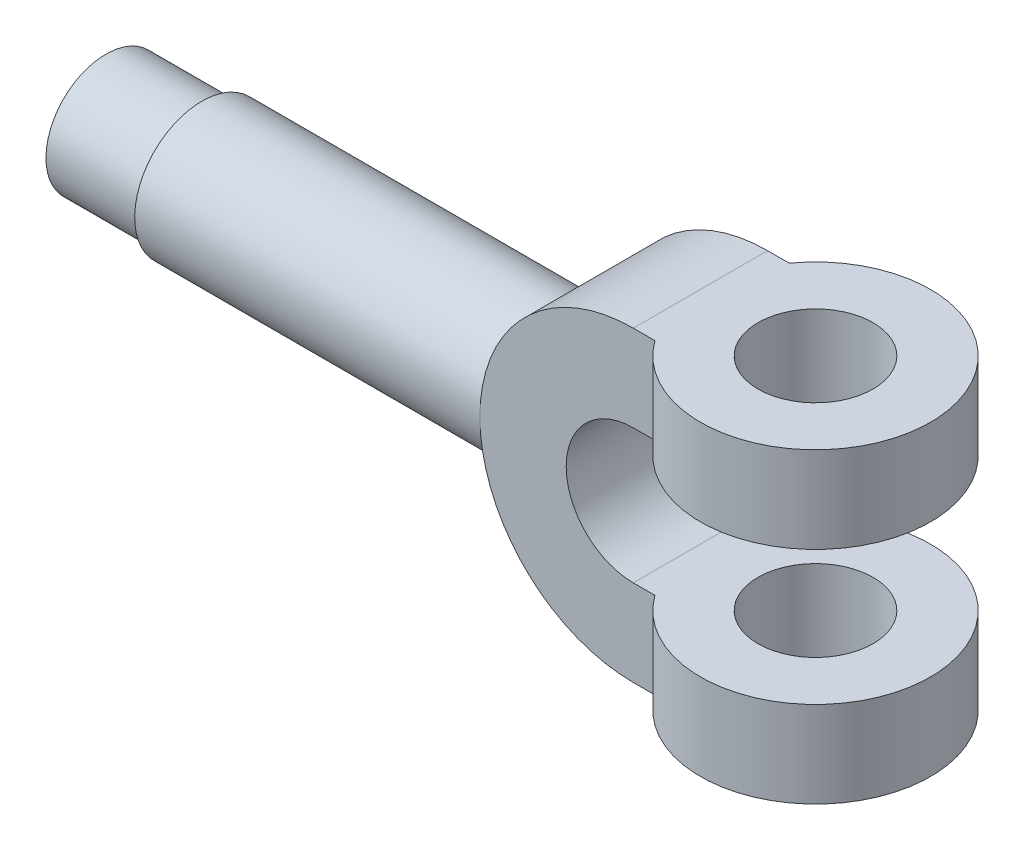
SolidWorks part; units mm, degrees
material "Gray Cast Iron"
ref_plane "Front Plane" through (0, 0, 0) normal (0, 0, 1) x (1, 0, 0)
ref_plane "Top Plane" through (0, 0, 0) normal (0, 1, 0) x (1, 0, 0)
ref_plane "Right Plane" through (0, 0, 0) normal (1, 0, 0) x (0, 0, -1)
sketch "Sketch2" plane through (0, 0, 0) normal (0, 1, 0) x (1, 0, 0)
  circle A0 centre (0, 0) radius 24
  circle A1 centre (0, 0) radius 12
  dimension "D1" = 48
  dimension "D2" = 24
extrude "Boss-Extrude2" add sketch "Sketch2" along normal blind 18
ref_plane "Plane1" through (0, 46, 0) normal (0, 1, 0) x (1, 0, 0)
sketch "Sketch3" plane through (0, 46, 0) normal (0, 1, 0) x (1, 0, 0)
  circle A0 centre (0, 0) radius 24 construction
  circle A1 centre (0, 0) radius 12 construction
  circle A2 centre (0, 0) radius 24
  circle A3 centre (0, 0) radius 12
extrude "Boss-Extrude3" add sketch "Sketch3" along normal blind 18 separate body
sketch "Sketch4" plane through (0, 0, 0) normal (0, 0, 1) x (1, 0, 0)
  line L2 (-24, 46) -> (24, 46) construction
  line L3 (24, 18) -> (-24, 18) construction
  line L4 (24, 64) -> (-24, 64) construction
  line L5 (-24, 0) -> (24, 0) construction
  line L6 (-24, 64) -> (-24, 46) construction
  line L7 (-24, 18) -> (-24, 0) construction
  line L8 (-24, 64) -> (-24, 46)
  line L9 (-24, 18) -> (-24, 0)
  arc A0 (-24, 46) -> (-24, 18) centre (-24, 32) ccw
  arc A1 (-24, 64) -> (-24, 0) centre (-24, 32) ccw
extrude "Boss-Extrude4" add sketch "Sketch4" along normal mid plane 28 separate body contours A1 L9 A0 L8
sketch "Sketch5" plane through (0, 0, 0) normal (0, 0, 1) x (1, 0, 0)
  line L0 (-1038, 32) -> (48962, 32) construction
  line L1 (-24, -968) -> (-24, 49032) construction
  line L4 (-52.775, 46) -> (-128, 46)
  line L6 (-128, 32) -> (-56, 32)
  line L7 (-128, 46) -> (-128, 32)
  arc A0 (-24, 46) -> (-24, 18) centre (-24, 32) ccw construction
  arc A1 (-52.775, 46) -> (-56, 32) centre (-24, 32) ccw
  arc A2 (-24, 64) -> (-24, 0) centre (-24, 32) ccw construction
  point P6 (-38, 32)
  dimension "D1" = 14
  dimension "D2" = 104
revolve "Revolve1" add sketch "Sketch5" angle 360 about L6
sketch "Sketch6" plane through (-128, 0, 0) normal (-1, 0, 0) x (0, 0, 1)
  circle A0 centre (0, 32) radius 12.5
  dimension "D1" = 25
extrude "Boss-Extrude5" add sketch "Sketch6" along normal blind 20
sketch "Sketch7" plane through (0, 64, 0) normal (0, 1, 0) x (1, 0, 0)
  line L0 (-24, 14) -> (-19.4936, 14)
  line L5 (-24, 14) -> (-24, 0)
  circle A0 centre (0, 0) radius 24 construction
  arc A1 (-19.4936, 14) -> (-24, 0) centre (0, 0) ccw
extrude "Boss-Extrude7" add sketch "Sketch7" against normal blind 18 contours L5 A1 L0
mirror "Mirror1" about plane through (0, 0, 0) normal (0, 0, 1) of "Boss-Extrude7"
sketch "Sketch8" plane through (0, 0, 0) normal (0, -1, 0) x (1, 0, 0)
  line L0 (-24, 14) -> (-19.4936, 14)
  line L1 (-24, 14) -> (-19.4936, 14) construction
  line L2 (-24, 14) -> (-24, 0)
  line L3 (-24, 14) -> (-24, -14) construction
  circle A0 centre (0, 0) radius 24 construction
  arc A1 (-19.4936, 14) -> (-24, 0) centre (0, 0) ccw
extrude "Boss-Extrude8" add sketch "Sketch8" against normal blind 18
mirror "Mirror2" about plane through (0, 0, 0) normal (0, 0, 1) of "Boss-Extrude8"
